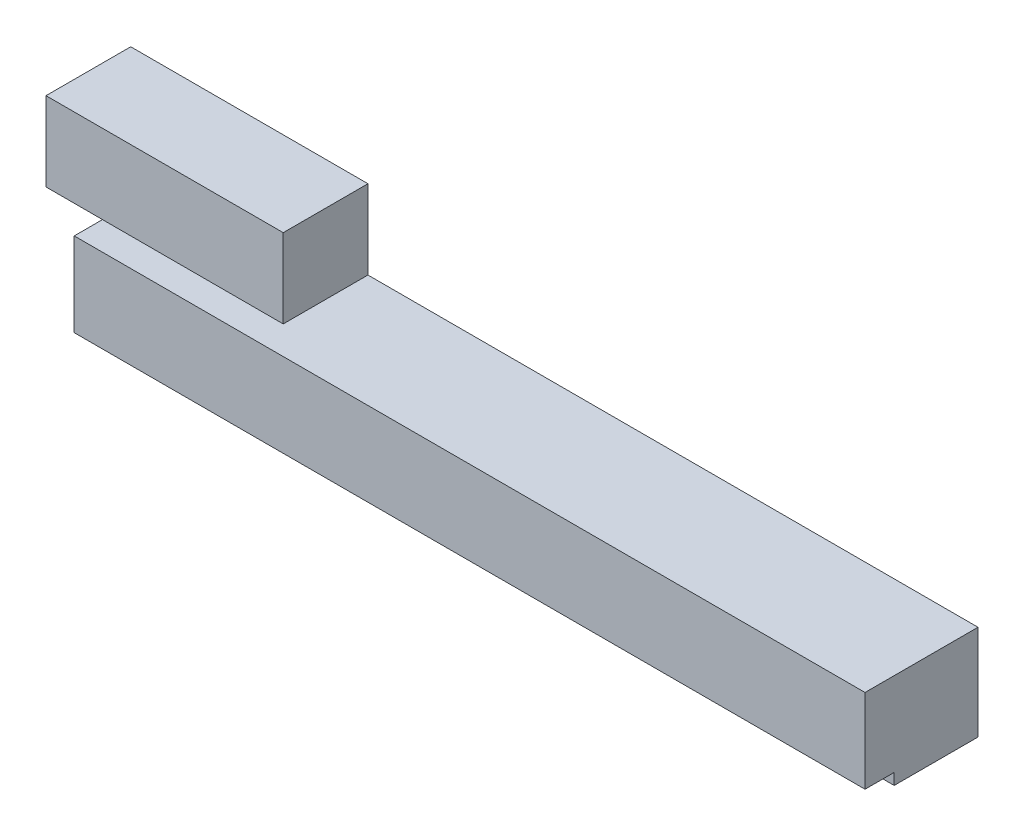
SolidWorks part; units mm, degrees
ref_plane "Front Plane" through (0, 0, 0) normal (0, 0, 1) x (1, 0, 0)
ref_plane "Top Plane" through (0, 0, 0) normal (0, 1, 0) x (1, 0, 0)
ref_plane "Right Plane" through (0, 0, 0) normal (1, 0, 0) x (0, 0, -1)
sketch "Sketch1" plane through (0, 0, 0) normal (1, 0, 0) x (0, 0, -1)
  line L0 (-10, -6.42) -> (-4.84, -6.42)
  line L1 (-10, -8.42) -> (10, -8.42)
  line L2 (-10, -8.42) -> (-10, 8.42)
  line L3 (-10, 8.42) -> (10, 8.42)
  line L4 (10, -8.42) -> (10, 8.42)
  line L5 (-10, -8.42) -> (10, 8.42) construction
  line L6 (-10, 8.42) -> (10, -8.42) construction
  line L7 (-4.84, -6.42) -> (-4.84, -8.42)
  point P0 (0, 0)
  dimension "D1" = 16.84
  dimension "D2" = 20
  dimension "D3" = 2
  dimension "D4" = 5.16
extrude "Boss-Extrude1" add sketch "Sketch1" along normal blind 140 contours L0 L7 L1 L4 L3 L2
sketch "Sketch2" plane through (0, 8.42, 0) normal (0, 1, 0) x (1, 0, 0)
  line L0 (140, -10) -> (140, 10) construction
  line L1 (-10, 10) -> (32, 10)
  line L2 (-10, 10) -> (-10, -5)
  line L3 (-10, -5) -> (32, -5)
  line L4 (32, 10) -> (32, -5)
  line L5 (140, -10) -> (0, -10) construction
  dimension "D1" = 42
  dimension "D2" = 15
  dimension "D3" = 108
  dimension "D4" = 5
extrude "Boss-Extrude2" add sketch "Sketch2" along normal blind 14
